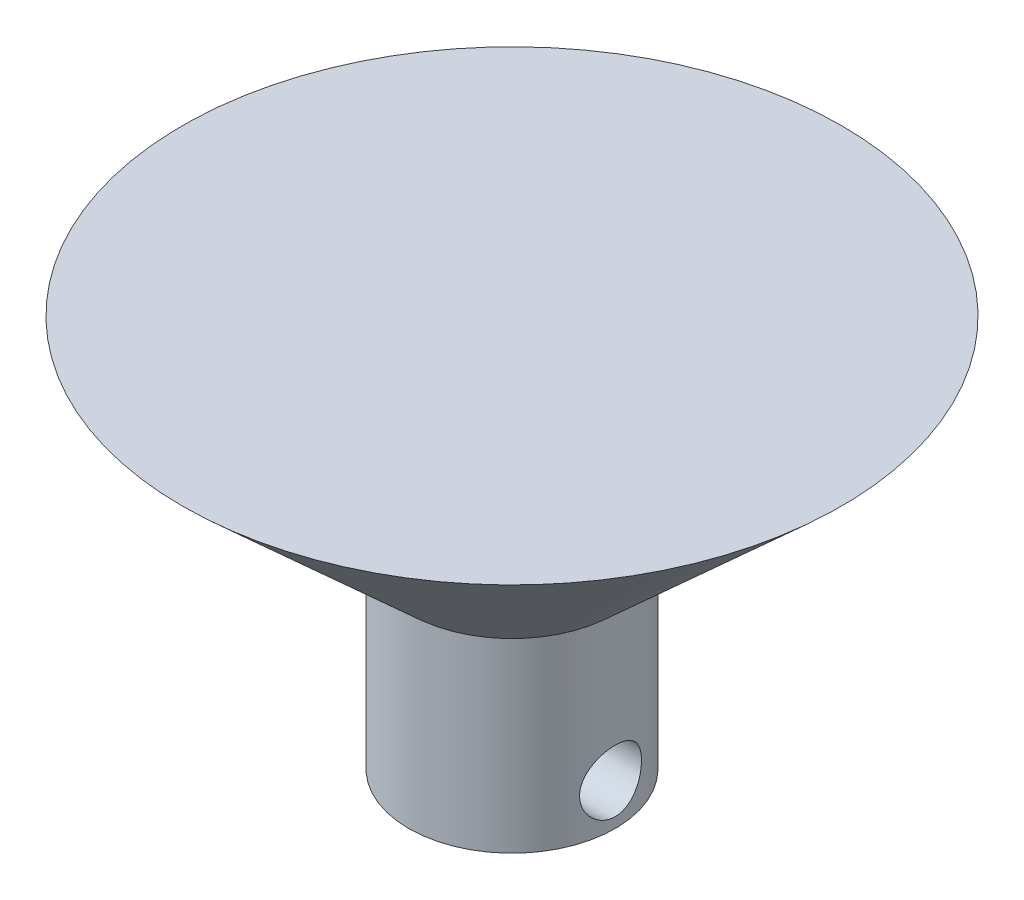
SolidWorks part; units mm, degrees
ref_plane "Front Plane" through (0, 0, 0) normal (0, 0, 1) x (1, 0, 0)
ref_plane "Top Plane" through (0, 0, 0) normal (0, 1, 0) x (1, 0, 0)
ref_plane "Right Plane" through (0, 0, 0) normal (1, 0, 0) x (0, 0, -1)
sketch "Sketch1" plane through (0, 0, 0) normal (0, 1, 0) x (1, 0, 0)
  circle A0 centre (0, 0) radius 5
  dimension "D1" = 10
extrude "body" add sketch "Sketch1" along normal blind 9
sketch "Sketch2" plane through (0, 0, 0) normal (1, 0, 0) x (0, 0, -1)
  circle A0 centre (0, 2) radius 1.5
  dimension "D1" = 2
  dimension "D2" = 3
extrude "pin insert" cut sketch "Sketch2" against normal through all and the other way through all
ref_plane "contact plane" through (0, 19, 0) normal (0, 1, 0) x (1, 0, 0)
sketch "head SA" plane through (0, 19, 0) normal (0, 1, 0) x (1, 0, 0)
  circle A0 centre (0, 0) radius 15.958
  dimension "D1" = 31.916
loft "cone" add profiles "head SA" section "head SA" section face at (0, 9, 5)
